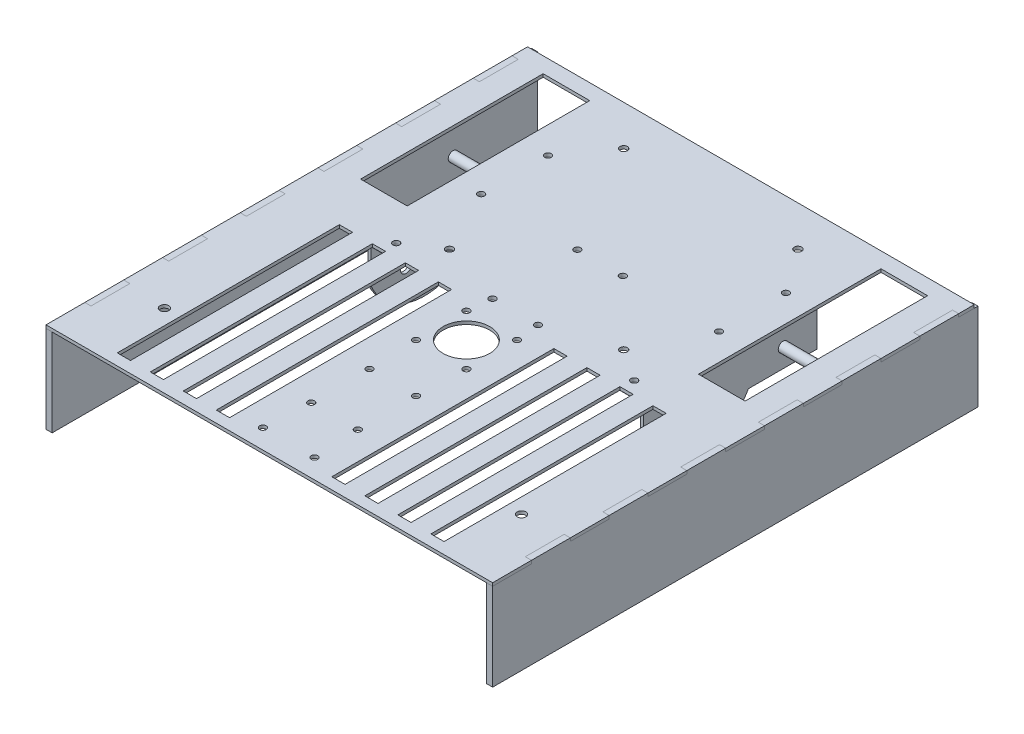
SolidWorks part; units mm, degrees
ref_plane "Front Plane" through (0, 0, 0) normal (0, 0, 1) x (1, 0, 0)
ref_plane "Top Plane" through (0, 0, 0) normal (0, 1, 0) x (1, 0, 0)
ref_plane "Right Plane" through (0, 0, 0) normal (1, 0, 0) x (0, 0, -1)
sketch "Sketch2" plane through (0, 0, 0) normal (0, 1, 0) x (1, 0, 0)
  line L7 (-172.2662, -88.2141) -> (57.7338, -88.2141)
  line L8 (17.7338, 151.7859) -> (41.7338, 151.7859)
  line L9 (57.7338, -88.2141) -> (57.7338, -68.2141)
  line L10 (57.7338, -68.2141) -> (54.5588, -68.2141)
  line L11 (54.5588, -68.2141) -> (54.5588, -48.2141)
  line L12 (54.5588, -48.2141) -> (57.7338, -48.2141)
  line L13 (-172.2662, -88.2141) -> (-172.2662, -68.2141)
  line L14 (-172.2662, -68.2141) -> (-169.0912, -68.2141)
  line L15 (-169.0912, -68.2141) -> (-169.0912, -48.2141)
  line L16 (-169.0912, -48.2141) -> (-172.2662, -48.2141)
  line L17 (-172.2662, -48.2141) -> (-172.2662, -28.2141)
  line L18 (-172.2662, -28.2141) -> (-169.0912, -28.2141)
  line L19 (-169.0912, -28.2141) -> (-169.0912, -8.2141)
  line L20 (-169.0912, -8.2141) -> (-172.2662, -8.2141)
  line L21 (57.7338, -28.2141) -> (54.5588, -28.2141)
  line L22 (54.5588, -28.2141) -> (54.5588, -8.2141)
  line L23 (54.5588, -8.2141) -> (57.7338, -8.2141)
  line L24 (57.7338, -48.2141) -> (57.7338, -28.2141)
  line L25 (-172.2662, -8.2141) -> (-172.2662, 11.7859)
  line L26 (-172.2662, 11.7859) -> (-169.0912, 11.7859)
  line L27 (-169.0912, 11.7859) -> (-169.0912, 31.7859)
  line L28 (-169.0912, 31.7859) -> (-172.2662, 31.7859)
  line L29 (57.7338, 11.7859) -> (54.5588, 11.7859)
  line L30 (54.5588, 11.7859) -> (54.5588, 31.7859)
  line L31 (54.5588, 31.7859) -> (57.7338, 31.7859)
  line L32 (57.7338, -8.2141) -> (57.7338, 11.7859)
  line L33 (-172.2662, 31.7859) -> (-172.2662, 51.7859)
  line L34 (-172.2662, 51.7859) -> (-169.0912, 51.7859)
  line L35 (-169.0912, 51.7859) -> (-169.0912, 71.7859)
  line L36 (-169.0912, 71.7859) -> (-172.2662, 71.7859)
  line L37 (57.7338, 51.7859) -> (54.5588, 51.7859)
  line L38 (54.5588, 51.7859) -> (54.5588, 71.7859)
  line L39 (54.5588, 71.7859) -> (57.7338, 71.7859)
  line L40 (57.7338, 31.7859) -> (57.7338, 51.7859)
  line L45 (17.7338, 151.7859) -> (17.7338, 57.7859)
  line L46 (17.7338, 57.7859) -> (41.7338, 57.7859)
  line L47 (41.7338, 151.7859) -> (41.7338, 57.7859)
  line L48 (-156.2662, 151.7859) -> (-132.2662, 151.7859)
  line L49 (-156.2662, 151.7859) -> (-156.2662, 57.7859)
  line L50 (-156.2662, 57.7859) -> (-132.2662, 57.7859)
  line L51 (-132.2662, 151.7859) -> (-132.2662, 57.7859)
  line L52 (-172.2662, 71.7859) -> (-172.2662, 91.7859)
  line L53 (-172.2662, 91.7859) -> (-169.0912, 91.7859)
  line L54 (-169.0912, 91.7859) -> (-169.0912, 111.7859)
  line L55 (-169.0912, 111.7859) -> (-172.2662, 111.7859)
  line L56 (57.7338, 91.7859) -> (54.5588, 91.7859)
  line L57 (54.5588, 91.7859) -> (54.5588, 111.7859)
  line L58 (54.5588, 111.7859) -> (57.7338, 111.7859)
  line L59 (57.7338, 71.7859) -> (57.7338, 91.7859)
  line L63 (-172.2662, 111.7859) -> (-172.2662, 131.7859)
  line L64 (-172.2662, 131.7859) -> (-169.0912, 131.7859)
  line L65 (-169.0912, 131.7859) -> (-169.0912, 151.7859)
  line L66 (-169.0912, 151.7859) -> (-172.2662, 151.7859)
  line L67 (57.7338, 131.7859) -> (54.5588, 131.7859)
  line L68 (54.5588, 131.7859) -> (54.5588, 151.7859)
  line L69 (54.5588, 151.7859) -> (57.7338, 151.7859)
  line L70 (57.7338, 111.7859) -> (57.7338, 131.7859)
  line L71 (57.7338, 151.7859) -> (57.7338, 159.7859)
  line L72 (57.7338, 159.7859) -> (-172.2662, 159.7859)
  line L73 (-172.2662, 159.7859) -> (-172.2662, 151.7859)
  dimension "D1" = 3.175
  dimension "D2" = 20
  dimension "D3" = 20
  dimension "D4" = 3.175
  dimension "D6" = 230
  dimension "D8" = 24
  dimension "D9" = 24
  dimension "D10" = 16
  dimension "D11" = 16
  dimension "D13" = 94
  dimension "D7" = 8
  dimension "D12" = 8
  dimension "D5" = 6
extrude "Boss-Extrude1" add sketch "Sketch2" along normal blind 1.6
ref_plane "Plane3" through (-57.2662, 0, 0) normal (-1, 0, 0) x (0, 0, 1)
sketch "Sketch3" plane through (-169.0912, 0, 0) normal (-1, 0, 0) x (0, 0, 1)
  line L0 (68.2141, 1.6) -> (68.2141, 0)
  line L1 (68.2141, 0) -> (88.2141, 0)
  line L2 (88.2141, 0) -> (88.2141, -45)
  line L3 (68.2141, 1.6) -> (48.2141, 1.6)
  line L4 (48.2141, 1.6) -> (48.2141, 0)
  line L5 (48.2141, 0) -> (28.2141, 0)
  line L6 (28.2141, 0) -> (28.2141, 1.6)
  line L7 (28.2141, 1.6) -> (8.2141, 1.6)
  line L8 (8.2141, 1.6) -> (8.2141, 0)
  line L9 (8.2141, 0) -> (-11.7859, 0)
  line L10 (-11.7859, 0) -> (-11.7859, 1.6)
  line L11 (-91.7859, 0) -> (-91.7859, 1.6)
  line L12 (-11.7859, 1.6) -> (-31.7859, 1.6)
  line L13 (-31.7859, 1.6) -> (-31.7859, 0)
  line L14 (-31.7859, 0) -> (-51.7859, 0)
  line L15 (-51.7859, 0) -> (-51.7859, 1.6)
  line L16 (-51.7859, 1.6) -> (-71.7859, 1.6)
  line L17 (-71.7859, 1.6) -> (-71.7859, 0)
  line L18 (-71.7859, 0) -> (-91.7859, 0)
  line L21 (-91.7859, 1.6) -> (-111.7859, 1.6)
  line L22 (-111.7859, 1.6) -> (-111.7859, 0)
  line L25 (-111.7859, 0) -> (-131.7859, 0)
  line L26 (-151.7859, 0) -> (-131.7859, 0) construction
  line L27 (-131.7859, 1.6) -> (-131.7859, 0) construction
  line L28 (-131.7859, 0) -> (-131.7859, 1.6)
  line L29 (-131.7859, 1.6) -> (-151.7859, 1.6)
  line L30 (-151.7859, 1.6) -> (-151.7859, 0)
  line L31 (-151.7859, 1.6) -> (-151.7859, 0) construction
  line L32 (-151.7859, 0) -> (-161.732, 0)
  line L33 (-161.732, 0) -> (-161.732, -45)
  line L34 (-161.732, -45) -> (88.2141, -45)
extrude "Boss-Extrude2" add sketch "Sketch3" along normal blind 3.175 separate body
sketch "Sketch4" plane through (0, 0, 0) normal (0, -1, 0) x (1, 0, 0)
  line L0 (-128.2662, -122.8126) -> (-128.2662, -33.5103)
  line L1 (-128.2662, -122.8126) -> (-110.4256, -122.8126)
  line L2 (-128.2662, -33.5103) -> (-110.4287, -33.5103)
  line L5 (-64.765, -32.9867) -> (-64.765, -87.1773)
  line L6 (-64.765, -32.9867) -> (-73.1795, -32.9867)
  line L7 (-64.765, -87.1773) -> (-73.1795, -87.1773)
  line L9 (-110.4287, -33.5103) -> (-110.4287, -55.4044)
  line L10 (-110.4287, -55.4044) -> (-73.1795, -55.4044)
  line L11 (-73.1795, -55.4044) -> (-73.1795, -32.9867)
  line L12 (-73.1795, -87.1773) -> (-73.1795, -65.4044)
  line L13 (-73.1795, -65.4044) -> (-110.4256, -65.4044)
  line L14 (-110.4256, -65.4044) -> (-110.4256, -122.8126)
extrude "Boss-Extrude3" add sketch "Sketch4" along normal blind 1.6129 separate body
sketch "Sketch6" plane through (-128.2662, 113.8349, 0) normal (1, 0, 0) x (0, -1, 0)
  line L0 (115.4478, 33.5103) -> (113.8349, 33.5103)
  line L1 (113.8349, 33.5103) -> (113.8349, 122.8126)
  line L4 (132.89, 33.5103) -> (115.4478, 33.5103)
  line L7 (135.5889, 122.8126) -> (113.8349, 122.8126)
  line L8 (113.8349, 57.7859) -> (113.8349, 151.7859) construction
  line L10 (115.4478, 122.8126) -> (113.8349, 122.8126) construction
  line L11 (135.5889, 122.8126) -> (135.5889, 87.5048)
  circle A2 centre (133.4041, 73.86) radius 1.27
  circle A4 centre (133.4041, 51.6858) radius 3
  circle A5 centre (125.8349, 105.4126) radius 2.55
  circle A6 centre (123.1933, 51.6858) radius 1.27
  circle A8 centre (143.6149, 51.6858) radius 1.27
  arc A10 (135.5889, 87.5048) -> (132.89, 33.5103) centre (121.2431, 61.1572) cw
  dimension "D1" = 5.1
  dimension "D3" = 17.4
  dimension "D4" = 6
  dimension "D2" = 12
extrude "Boss-Extrude4" add sketch "Sketch6" along normal blind 1.6129
sketch "Sketch7" plane through (0, -1.6129, 0) normal (0, -1, 0) x (1, 0, 0)
  line L0 (-172.2662, 88.2141) -> (57.7338, 88.2141) construction
  line L1 (-57.2662, -1.2799) -> (-57.2662, -25.2799)
  line L31 (-124.414, -31.9949) -> (-124.414, 82.3679)
  line L32 (-141.414, -31.9949) -> (-134.6033, -31.9949)
  line L33 (-141.414, -31.9949) -> (-141.414, 82.3679)
  line L34 (-141.414, 82.3679) -> (-134.6033, 82.3679)
  line L35 (-134.6033, -31.9949) -> (-134.6033, 82.3679)
  line L36 (-124.414, -31.9949) -> (-117.6033, -31.9949)
  line L37 (-124.414, 82.3679) -> (-117.6033, 82.3679)
  line L38 (-117.6033, -31.9949) -> (-117.6033, 82.3679)
  line L39 (-107.414, -31.9949) -> (-107.414, 82.3679)
  line L40 (-107.414, -31.9949) -> (-100.6033, -31.9949)
  line L41 (-107.414, 82.3679) -> (-100.6033, 82.3679)
  line L42 (-100.6033, -31.9949) -> (-100.6033, 82.3679)
  line L43 (-90.414, -31.9949) -> (-90.414, 82.3679)
  line L44 (-90.414, -31.9949) -> (-83.6033, -31.9949)
  line L45 (-90.414, 82.3679) -> (-83.6033, 82.3679)
  line L46 (-83.6033, -31.9949) -> (-83.6033, 82.3679)
  circle A0 centre (-118.541, -82.125) radius 1.7
  circle A1 centre (-118.541, -38.4299) radius 1.7
  circle A2 centre (-68.9723, -38.4299) radius 1.7
  circle A3 centre (-68.9723, -82.125) radius 1.7
  circle A4 centre (-118.541, -116.5476) radius 1.7
  circle A5 centre (-102.1184, -49.4299) radius 1.9
  circle A6 centre (-102.1184, -139.1299) radius 1.9
  circle A7 centre (-149.2312, 50.2851) radius 2.25
  circle A8 centre (-70.2662, -0.2799) radius 1.7
  circle A9 centre (-70.2662, -26.2799) radius 1.7
  arc A11 (-57.2662, -1.2799) -> (-57.2662, -25.2799) centre (-57.2662, -13.2799) ccw
  circle A12 centre (-70.5662, 78.2141) radius 1.7
  circle A13 centre (-69.2662, 24.6349) radius 1.7
  circle A14 centre (-69.2662, 54.6349) radius 1.7
  point P19 (-57.264, -94.2799)
  point P29 (-57.2662, 88.2141)
  dimension "D3" = 3.4
  dimension "D4" = 3.4
  dimension "D5" = 3.4
  dimension "D6" = 3.4
  dimension "D1" = 3.4
  dimension "D2" = 3.8
  dimension "D8" = 3.8
  dimension "D9" = 4.5
  dimension "D12" = 3.4
  dimension "D13" = 3.4
  dimension "D14" = 12
  dimension "D20" = 3.4
  dimension "D23" = 3.4
  dimension "D24" = 3.4
  dimension "D7" = 89.7
  dimension "D10" = 91.965
  dimension "D11" = 144.565
  dimension "D15" = 13
  dimension "D16" = 68
  dimension "D17" = 13
  dimension "D18" = 26
  dimension "D19" = 13
  dimension "D21" = 13.3
  dimension "D22" = 10
  dimension "D25" = 30
  dimension "D26" = 12
  dimension "D27" = 4
extrude "Cut-Extrude1" cut sketch "Sketch7" against normal blind 10
mirror "Mirror1" about plane through (-57.2662, 0, 0) normal (-1, 0, 0) of bodies 157 103 158
mirror "Mirror2" about plane through (-57.2662, 0, 0) normal (-1, 0, 0) of "Cut-Extrude1"
sketch "Sketch9" plane through (-156.2662, 0, 0) normal (1, 0, 0) x (0, 0, -1)
  circle A0 centre (105.4126, -12) radius 2.5
extrude "Boss-Extrude6" add sketch "Sketch9" along normal blind 189 separate body
equation "\"hardboard_width\"= 3.175"
equation "\"D1@Boss-Extrude1\"=\"hardboard_width\""
equation "\"D1@Sketch2\"=\"hardboard_width\""
equation "\"D4@Sketch2\"=\"hardboard_width\""
equation "\"D1@Boss-Extrude2\"=\"hardboard_width\""
equation "\"steel_24g_thickness\"= 0.5"
equation "\"m3_clearance_hole\"= 3.4"
equation "\"D3@Sketch7\"=\"m3_clearance_hole\""
equation "\"D4@Sketch7\"=\"m3_clearance_hole\""
equation "\"D5@Sketch7\"=\"m3_clearance_hole\""
equation "\"D6@Sketch7\"=\"m3_clearance_hole\""
equation "\"steel_16g_thickness\"=1.6129"
equation "\"D1@Boss-Extrude3\"=\"steel_16g_thickness\""
equation "\"D1@Boss-Extrude4\"=\"steel_16g_thickness\""
equation "\"D1@Sketch7\"=\"m3_clearance_hole\""
equation "\"D12@Sketch7\"=\"m3_clearance_hole\""
equation "\"D20@Sketch7\"=\"m3_clearance_hole\""
equation "\"D23@Sketch7\"=\"m3_clearance_hole\""
equation "\"D24@Sketch7\"=\"m3_clearance_hole\""
